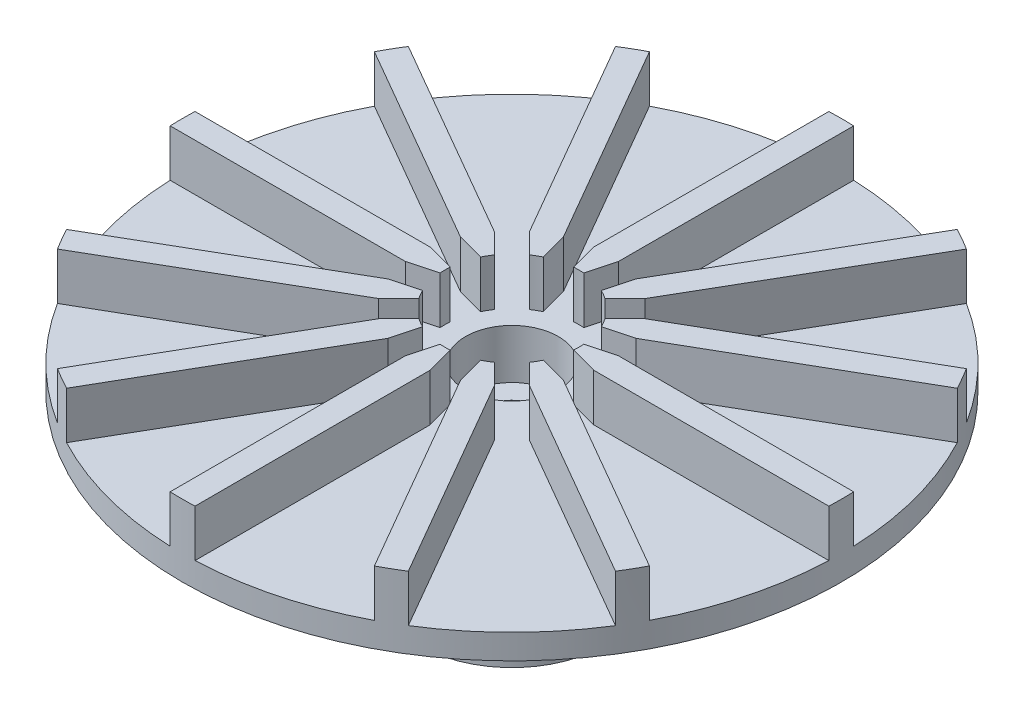
SolidWorks part; units mm, degrees
ref_plane "Front Plane" through (0, 0, 0) normal (0, 0, 1) x (1, 0, 0)
ref_plane "Top Plane" through (0, 0, 0) normal (0, 1, 0) x (1, 0, 0)
ref_plane "Right Plane" through (0, 0, 0) normal (1, 0, 0) x (0, 0, -1)
sketch "Sketch1" plane through (0, 0, 0) normal (0, 1, 0) x (1, 0, 0)
  circle A0 centre (0, 0) radius 26.6319
  dimension "D1" = 53.2638
extrude "base" add sketch "Sketch1" along normal blind 2
sketch "Sketch2" plane through (0, 0, 0) normal (0, -1, 0) x (1, 0, 0)
  circle A0 centre (0, 0) radius 7.5
  dimension "D1" = 15
extrude "boss" add sketch "Sketch2" along normal blind 14
sketch "Sketch3" plane through (0, 2, 0) normal (0, 1, 0) x (1, 0, 0)
  line L0 (5.4102, 0) -> (26.6319, 0) construction
  line L1 (5.3162, 1.004) -> (26.613, 1.004)
  line L2 (5.3162, -1.004) -> (26.613, -1.004)
  circle A0 centre (0, 0) radius 5.4102 construction
  circle A1 centre (0, 0) radius 26.6319 construction
  arc A2 (5.3162, -1.004) -> (5.3162, 1.004) centre (0, 0) ccw
  arc A3 (26.613, -1.004) -> (26.613, 1.004) centre (0, 0) ccw
  dimension "D1" = 10.8204
  dimension "D2" = 1.004
  dimension "D3" = 1.004
extrude "blade" add sketch "Sketch3" along normal blind 9.3026
pattern_circular "blade pattern" count 12 over 360 about axis through (0, 0, 0) along (0, 1, 0) of "blade"
sketch "Sketch5" plane through (0, 0, 0) normal (0, 0, 1) x (1, 0, 0)
  line L0 (-26.6319, 11.3026) -> (-26.6319, 5.81)
  line L2 (-26.6319, 5.81) -> (-5.4102, 11.3026)
  line L3 (-5.4102, 11.3026) -> (-26.6319, 11.3026)
  line L4 (12.437, 2) -> (1.004, 2) construction
  line L5 (0, 0) -> (0, 16.9753) construction
  dimension "D1" = 3.81
  dimension "D2" = 9.3026
  dimension "D3" = 26.6319
  dimension "D4" = 5.4102
revolve "angle trim" cut sketch "Sketch5" angle 360 about L5
sketch "Sketch6" plane through (0, -14, 0) normal (0, -1, 0) x (-1, 0, 0)
  circle A0 centre (0, 0) radius 4
  dimension "D1" = 8
extrude "bore_cut" cut sketch "Sketch6" against normal blind 9
sketch "Sketch7" plane through (0, -14, 0) normal (0, -1, 0) x (1, 0, 0)
  line L1 (-6, -1) -> (6, -1)
  line L2 (-6, -1) -> (-6, 1) construction
  line L3 (-6, 1) -> (6, 1)
  line L4 (6, -1) -> (6, 1) construction
  line L5 (-6, -1) -> (6, 1) construction
  line L6 (-6, 1) -> (6, -1) construction
  arc A0 (-6, 1) -> (-6, -1) centre (-6, 0) ccw
  arc A1 (6, -1) -> (6, 1) centre (6, 0) ccw
  point P0 (0, 0)
  dimension "D1" = 2
  dimension "D2" = 12
extrude "dowel cut" cut sketch "Sketch7" against normal blind 2
sketch "Sketch8" plane through (0, 2, 0) normal (0, 1, 0) x (1, 0, 0)
  circle A0 centre (0, 0) radius 3.75
  dimension "D1" = 7.5
extrude "bolt head recess" cut sketch "Sketch8" against normal blind 4
sketch "Sketch9" plane through (0, -2, 0) normal (0, 1, 0) x (1, 0, 0)
  circle A0 centre (0, 0) radius 2
  dimension "D1" = 4
extrude "bolt hole" cut sketch "Sketch9" against normal blind 14
sketch "Sketch11" plane through (0, 0, 0) normal (0, 0, 1) x (1, 0, 0)
  line L0 (0, 0) -> (0, 27.4) construction
  line L1 (0, 11.3026) -> (19.8566, 11.3026) construction
  line L3 (0, 5.8295) -> (26.6319, 5.81)
  line L5 (0, 5.8295) -> (0, 27.4)
  line L6 (0, 27.4) -> (26.6319, 5.81)
  line L8 (-23.5495, 2) -> (-26.613, 2) construction
  line L9 (-5.106, 11.3026) -> (-4.102, 11.3026) construction
  line L11 (26.6319, 0) -> (26.6319, 5.81) construction
  dimension "D1" = 5.4731
  dimension "D2" = 25.4
revolve "top angle (area based)" cut sketch "Sketch11" angle 360 about L5
sketch "Sketch12" plane through (0, 2, 0) normal (0, 1, 0) x (1, 0, 0)
  line L0 (0, 0) -> (25.7244, 6.8928) construction
  line L1 (0, 0) -> (26.6319, 0) construction
  line L2 (-0.2588, 0.9659) -> (0.2588, -0.9659)
  line L3 (25.4656, 7.8588) -> (25.9833, 5.9269)
  line L4 (25.4656, 7.8588) -> (-0.2588, 0.9659)
  line L5 (25.9833, 5.9269) -> (0.2588, -0.9659)
  circle A0 centre (0, 0) radius 26.6319 construction
  arc A1 (-23.5495, 12.437) -> (-26.613, 1.004) centre (0, 0) ccw construction
  arc A2 (26.613, 1.004) -> (23.5495, 12.437) centre (0, 0) ccw construction
  dimension "D1" = 2
  dimension "D2" = 2
extrude "2mm slot cut" cut sketch "Sketch12" along normal blind 50.8
pattern_circular "slot pattern" count 12 over 360 about axis through (0, 0, 0) along (0, 1, 0) of "2mm slot cut"
equation "\"D1@Sketch1\"=\"d2\""
equation "\"D1@Sketch2\"=\"impeller boss diameter\""
equation "\"D1@boss\" = \"impeller boss depth\""
equation "\"D1@Sketch3\"=\"de\""
equation "\"D2@Sketch3\"=\"s\"/2"
equation "\"D3@Sketch3\"=\"s\"/2"
equation "\"D1@blade\" = \"b1\""
equation "\"D1@blade pattern\"=\"z\""
equation "\"D1@Sketch5\"=\"b2\""
equation "\"D2@Sketch5\"=\"b1\""
equation "\"D3@Sketch5\"=\"d2\"/2"
equation "\"D4@Sketch5\"=\"de\"/2"
equation "\"D1@bore_cut\"= \"impeller shaft bore depth\""
equation "\"D1@Sketch6\"=\"impeller shaft bore\""
equation "\"D1@Sketch7\"=\"impeller dowel diameter\""
equation "\"D2@Sketch7\"=\"impeller dowel length\""
equation "\"D1@dowel cut\" = \"impeller dowel diameter\""
equation "\"D1\"= \"s\" / 2"
equation "\"D1@Sketch8\"=\"impeller bolt head diameter\""
equation "\"D1@bolt head recess\" = \"impeller bolt head depth\""
equation "\"D1@Sketch9\"=\"impeller screw hole bore\""
equation "\"bearing OD\" = 30mm"
equation "\"z\" = 12"
equation "\"de\" = 0.426in"
equation "\"d2\" = 2.097in"
equation "\"d_exit\" =\"b2\""
equation "\"theta\" = 15"
equation "\"b2\" = .15in"
equation "\"b1\" = \"b2\" + (\"d2\"/2 - \"de\"/2)*sin(\"theta\")"
equation "\"s\" = ( 1/\"z\")*(3.14*\"de\" - (3.14*(\"de\"^2) / (4*(\"b1\"))))"
equation "\"s_opening\" = (3.14*\"de\" - \"z\"*\"s\")/\"z\""
equation "\"area_eye\"=3.14*(\"de\"^2)/4"
equation "\"single_channel_area\"=\"s_opening\"*\"b1\""
equation "\"impeller upper clearance\"= .5mm"
equation "\"impeller horizontal clearance\"= .5mm"
equation "\"impeller bottom clearance\"= .5mm"
equation "\"impeller base thickness\"= 2mm"
equation "\"impeller boss depth\" = 14mm"
equation "\"impeller boss diameter\" = \"big seal ID\""
equation "\"impeller dowel diameter\" = 2mm"
equation "\"impeller bolt head diameter\" = 7.5mm"
equation "\"impeller bolt head depth\" = 4mm"
equation "\"impeller shaft bore\"= 8mm"
equation "\"impeller shaft bore depth\" = \"impeller boss depth\" + \"impeller base thickness\" - \"impeller bolt head depth\" - 3mm"
equation "\"impeller dowel length\" = 2mm*2 + \"impeller shaft bore\""
equation "\"impeller screw hole bore\" = 4mm"
equation "\"shaft impeller screw hole diameter\" = \"impeller screw hole bore\""
equation "\"bearing outer race thickness\"= 1mm"
equation "\"bearing ID\"= 10mm"
equation "\"bearing depth\"= 9mm"
equation "\"bearing inner race thickness\"= 1mm"
equation "\"small seal OD\" = 20mm"
equation "\"small seal ID\"= 8mm"
equation "\"small seal depth\" = 6mm"
equation "\"big seal OD\" = 30mm"
equation "\"big seal ID\"= 15mm"
equation "\"big seal depth\"= 8mm"
equation "\"D1@base\"=\"impeller base thickness\""
equation "\"area to cut\" = \"inlet area before cut\" - \"area_eye\""
equation "\"height to cut\" = \"area to cut\" / ((\"z\")* \"bit size\")"
equation "\"D1@Sketch11\"=\"height to cut\""
equation "\"bit size\" = 2mm"
equation "\"inlet area before cut\" = \"bit size\" * (\"z\") * \"b1\""
equation "\"shaft impeller section length\" = \"impeller shaft bore depth\""
equation "\"D1@Sketch12\"=\"bit size\""
equation "\"D2@Sketch12\"=\"bit size\""
equation "\"D1@slot pattern\"=\"z\""
